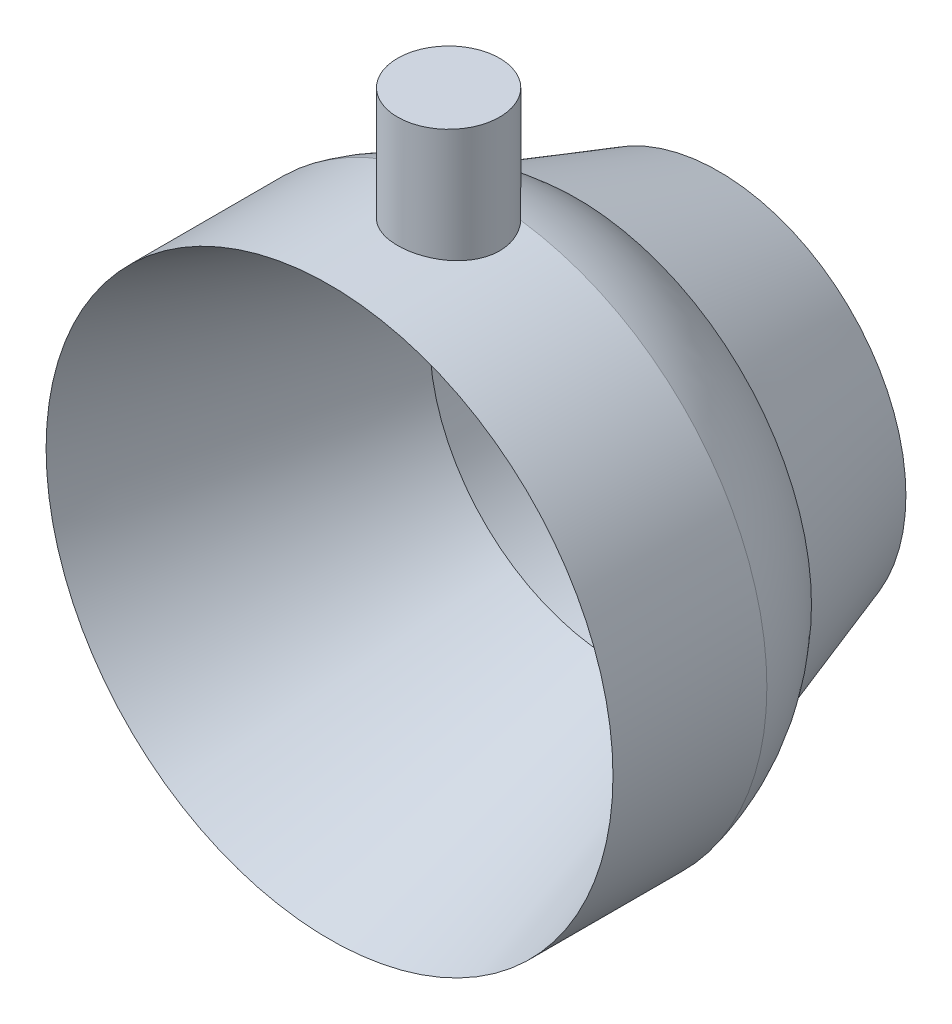
SolidWorks part; units mm, degrees
ref_plane "Front Plane" through (0, 0, 0) normal (0, 0, 1) x (1, 0, 0)
ref_plane "Top Plane" through (0, 0, 0) normal (0, 1, 0) x (1, 0, 0)
ref_plane "Right Plane" through (0, 0, 0) normal (1, 0, 0) x (0, 0, -1)
sketch "Sketch2" plane through (0, 0, 0) normal (0, 1, 0) x (1, 0, 0)
  line L0 (-11, 0) -> (-11, 6)
  line L1 (-11, 6) -> (-13.8011, -2.3515)
  line L3 (0, 0) -> (0, 14.7297) construction
  line L4 (-11, 0) -> (-16.6624, -16.8827)
  line L5 (-16.6624, -16.8827) -> (-16.6624, -7.835)
  arc A0 (-16.6624, -7.835) -> (-13.8011, -2.3515) centre (-5.0361, -10.4135) cw
  point P9 (-16.4188, -4.6997)
  point P10 (-16.6624, -16.8827)
  dimension "D1" = 6
  dimension "D3" = 11
  dimension "D4" = 14
revolve "Revolve1" add sketch "Sketch2" angle 360 about L3
sketch "Sketch3" plane through (0, 0, 0) normal (0, 1, 0) x (1, 0, 0)
  line L1 (16.6624, -16.8827) -> (-16.6624, -16.8827) construction
  circle A0 centre (0, -9.8827) radius 3
  dimension "D1" = 6
  dimension "D2" = 7
extrude "Boss-Extrude1" add sketch "Sketch3" along normal blind 7 from offset 16.2
